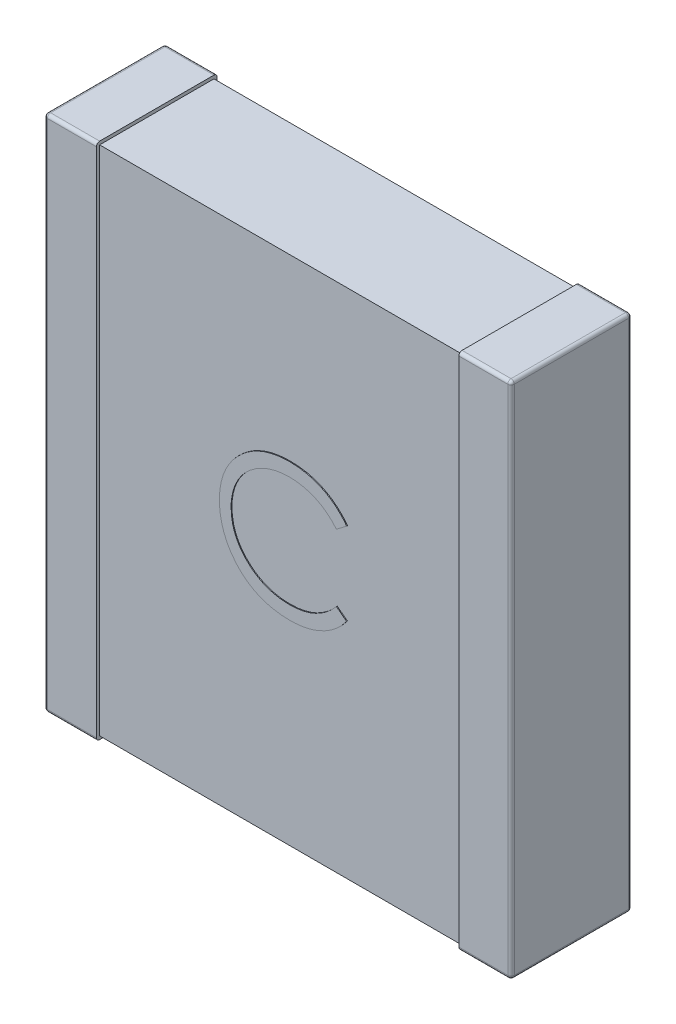
SolidWorks part; units mm, degrees
ref_plane "前视基准面" through (0, 0, 0) normal (0, 0, 1) x (1, 0, 0)
ref_plane "上视基准面" through (0, 0, 0) normal (0, 1, 0) x (1, 0, 0)
ref_plane "右视基准面" through (0, 0, 0) normal (1, 0, 0) x (0, 0, -1)
sketch "草图3" plane through (0, 0, 0) normal (0, 0, 1) x (1, 0, 0)
  line L0 (0, 4.2576) -> (0, -4.4067) construction
  line L1 (-2.86, 3.175) -> (-2.22, 3.175)
  line L2 (-2.86, 3.175) -> (-2.86, -3.175)
  line L3 (-2.86, -3.175) -> (-2.22, -3.175)
  line L4 (-2.22, 3.175) -> (-2.22, -3.175)
  line L5 (-2.86, 3.175) -> (-2.22, -3.175) construction
  line L6 (-2.86, -3.175) -> (-2.22, 3.175) construction
  line L7 (2.86, -3.175) -> (2.22, 3.175) construction
  line L8 (2.86, 3.175) -> (2.22, -3.175) construction
  line L9 (2.22, 3.175) -> (2.22, -3.175)
  line L10 (2.86, -3.175) -> (2.22, -3.175)
  line L11 (2.86, 3.175) -> (2.86, -3.175)
  line L12 (2.86, 3.175) -> (2.22, 3.175)
  point P0 (-2.54, 0)
  point P12 (2.54, 0)
  dimension "D1" = 0.64
  dimension "D2" = 6.35
  dimension "D3" = 2.86
extrude "凸台-拉伸1" add sketch "草图3" along normal blind 1.44 and the other way blind 0.04
sketch "草图5" plane through (0, 0, 0) normal (1, 0, 0) x (0, 0, -1)
  line L0 (0, 3.135) -> (0, -3.135)
  line L1 (0, -3.135) -> (-1.4, -3.135)
  line L2 (-1.4, -3.135) -> (-1.4, 3.135)
  line L3 (-1.4, 3.135) -> (0, 3.135)
  dimension "D1" = 6.27
  dimension "D2" = 1.4
extrude "凸台-拉伸3" add sketch "草图5" along normal mid plane 4.56
fillet "圆角3" radius 0.04 16 edges at (2.86, 0, -0.04) (2.86, -3.175, 0.7) (2.86, 0, 1.44) (2.86, 3.175, 0.7) (-2.86, 0, -0.04) (-2.86, 3.175, 0.7) (-2.86, 0, 1.44) (-2.86, -3.175, 0.7) (2.54, 3.175, -0.04) (2.54, -3.175, -0.04) (2.54, -3.175, 1.44) (2.54, 3.175, 1.44) (-2.54, -3.175, -0.04) (-2.54, -3.175, 1.44) (-2.54, 3.175, -0.04) (-2.54, 3.175, 1.44)
sketch "草图6" plane through (0, 0, 1.4) normal (0, 0, 1) x (1, 0, 0)
  text T0 "C" font "Century Gothic" height 1.6
extrude "凸台-拉伸4" add sketch "草图6" along normal blind 0.01
